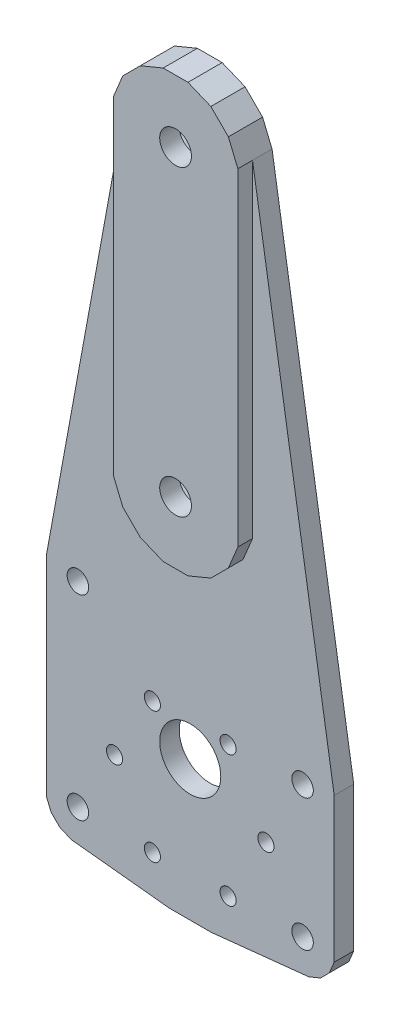
SolidWorks part; units mm, degrees
ref_plane "前视基准面" through (0, 0, 0) normal (0, 0, 1) x (1, 0, 0)
ref_plane "上视基准面" through (0, 0, 0) normal (0, 1, 0) x (1, 0, 0)
ref_plane "右视基准面" through (0, 0, 0) normal (1, 0, 0) x (0, 0, -1)
other "Configuration Table"
sketch "Profile_1" plane through (0, 0, 0) normal (0, 0, 1) x (1, 0, 0)
  line L0 (10.8091, 7.2224) -> (7.2224, 10.8091)
  line L1 (7.2224, 10.8091) -> (2.5362, 12.7502)
  line L2 (2.5362, 12.7502) -> (-2.5362, 12.7502)
  line L3 (-2.5362, 12.7502) -> (-7.2224, 10.8091)
  line L4 (-7.2224, 10.8091) -> (-10.8091, 7.2224)
  line L5 (-10.8091, 7.2224) -> (-12.7502, 2.5362)
  line L6 (-12.7502, 2.5362) -> (-29.4732, -88.7124)
  line L7 (-29.4732, -88.7124) -> (-29.4732, -131.2876)
  line L8 (-29.4732, -131.2876) -> (-28.4877, -133.6668)
  line L9 (-28.4877, -133.6668) -> (-26.6668, -135.4877)
  line L10 (-26.6668, -135.4877) -> (-24.2876, -136.4732)
  line L11 (-24.2876, -136.4732) -> (-4.292, -138.5773)
  line L12 (-4.292, -138.5773) -> (4.292, -138.5773)
  line L13 (4.292, -138.5773) -> (24.2876, -136.4732)
  line L14 (24.2876, -136.4732) -> (26.6668, -135.4877)
  line L15 (26.6668, -135.4877) -> (28.4877, -133.6668)
  line L16 (28.4877, -133.6668) -> (29.4732, -131.2876)
  line L17 (29.4732, -131.2876) -> (29.4732, -101.7124)
  line L18 (29.4732, -101.7124) -> (12.7502, 2.5362)
  line L19 (12.7502, 2.5362) -> (10.8091, 7.2224)
  circle A0 centre (0, 0) radius 3.25
  circle A1 centre (0, -62) radius 3.25
  circle A2 centre (0, -110) radius 6.25
  circle A3 centre (-15.5, -117) radius 1.65
  circle A4 centre (-7.75, -103.5766) radius 1.65
  circle A5 centre (7.75, -103.5766) radius 1.65
  circle A6 centre (15.5, -117) radius 1.65
  circle A7 centre (7.75, -130.4234) radius 1.65
  circle A8 centre (-7.75, -130.4234) radius 1.65
  circle A9 centre (23, -130) radius 2.2
  circle A10 centre (-23, -130) radius 2.2
  circle A11 centre (23, -103) radius 2.2
  circle A12 centre (-23, -90) radius 2.2
extrude "Wheel_carrier" add sketch "Profile_1" along normal blind 4 from offset 0
sketch "Profile_2" plane through (0, 0, 0) normal (0, 0, 1) x (1, 0, 0)
  line L0 (-10.8091, -69.2224) -> (-7.2224, -72.8091)
  line L1 (-7.2224, -72.8091) -> (-2.5362, -74.7502)
  line L2 (-2.5362, -74.7502) -> (2.5362, -74.7502)
  line L3 (2.5362, -74.7502) -> (7.2224, -72.8091)
  line L4 (7.2224, -72.8091) -> (10.8091, -69.2224)
  line L5 (10.8091, -69.2224) -> (12.7502, -64.5362)
  line L6 (12.7502, -64.5362) -> (12.7502, 2.5362)
  line L7 (12.7502, 2.5362) -> (10.8091, 7.2224)
  line L8 (10.8091, 7.2224) -> (7.2224, 10.8091)
  line L9 (7.2224, 10.8091) -> (2.5362, 12.7502)
  line L10 (2.5362, 12.7502) -> (-2.5362, 12.7502)
  line L11 (-2.5362, 12.7502) -> (-7.2224, 10.8091)
  line L12 (-7.2224, 10.8091) -> (-10.8091, 7.2224)
  line L13 (-10.8091, 7.2224) -> (-12.7502, 2.5362)
  line L14 (-12.7502, 2.5362) -> (-12.7502, -64.5362)
  line L15 (-12.7502, -64.5362) -> (-10.8091, -69.2224)
  circle A0 centre (0, 0) radius 3.25
  circle A1 centre (0, -62) radius 3.25
extrude "Pivot_lands" add sketch "Profile_2" along normal blind 3 from offset 4
sketch "Profile_3" plane through (0, 0, 0) normal (0, 0, 1) x (1, 0, 0)
  line L0 (-5.175, -2.9878) -> (0, -5.9756)
  line L1 (0, -5.9756) -> (5.175, -2.9878)
  line L2 (5.175, -2.9878) -> (5.175, 2.9878)
  line L3 (5.175, 2.9878) -> (0, 5.9756)
  line L4 (0, 5.9756) -> (-5.175, 2.9878)
  line L5 (-5.175, 2.9878) -> (-5.175, -2.9878)
  line L6 (-5.175, -64.9878) -> (0, -67.9756)
  line L7 (0, -67.9756) -> (5.175, -64.9878)
  line L8 (5.175, -64.9878) -> (5.175, -59.0122)
  line L9 (5.175, -59.0122) -> (0, -56.0244)
  line L10 (0, -56.0244) -> (-5.175, -59.0122)
  line L11 (-5.175, -59.0122) -> (-5.175, -64.9878)
extrude "Nut_seats_C_D" cut sketch "Profile_3" along normal blind 3.01 from offset 0.01
